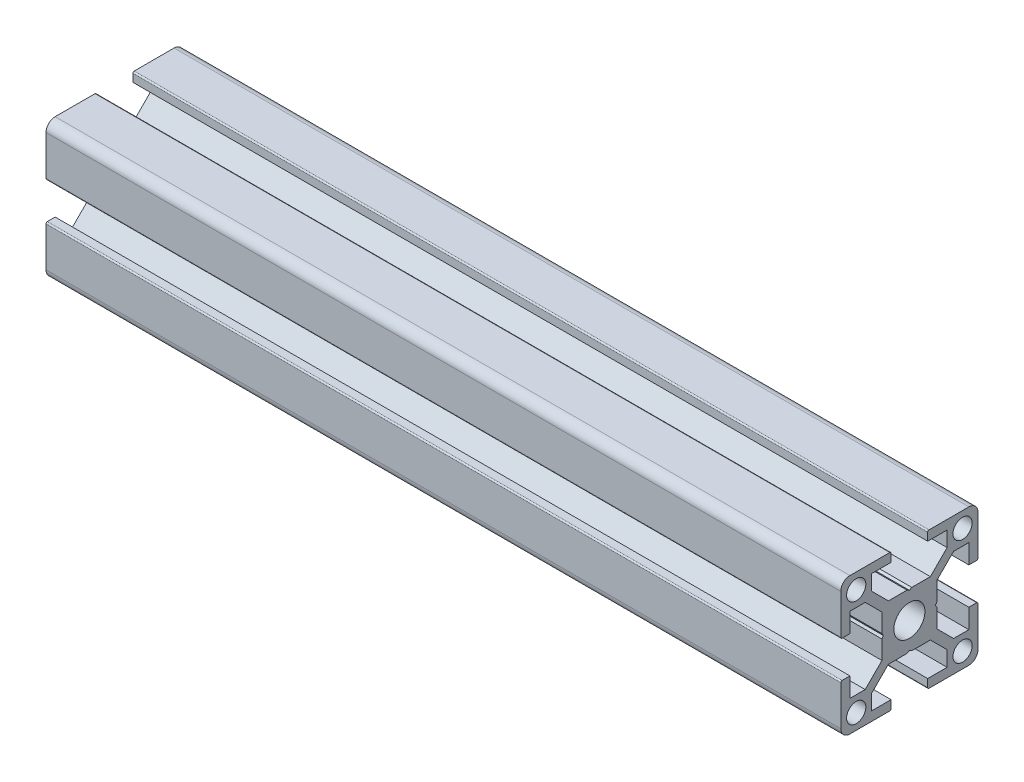
SolidWorks part; units mm, degrees
ref_plane "Front Plane" through (0, 0, 0) normal (0, 0, 1) x (1, 0, 0)
ref_plane "Top Plane" through (0, 0, 0) normal (0, 1, 0) x (1, 0, 0)
ref_plane "Right Plane" through (0, 0, 0) normal (1, 0, 0) x (0, 0, -1)
sketch "Sketch1" plane through (0, 0, 0) normal (0, 0, 1) x (1, 0, 0)
  line L0 (0, 0) -> (173.76, 0)
  dimension "D1" = 173.76
other "30xs6 30X30S6(1)"
ref_plane "Plane1" through (0, 0, 0) normal (1, 0, 0) x (0, 1, 0)
sketch "草图1" plane through (0, 0, 0) normal (1, 0, 0) x (0, 1, 0)
  line L0 (-14.7, 4) -> (-13, 4)
  line L1 (-13, 4) -> (-13, 8.25)
  line L2 (-13, 8.25) -> (-9.6642, 8.25)
  line L3 (-9.6642, 8.25) -> (-6, 4.5858)
  line L4 (-6, 4.5858) -> (-6, 0.5196)
  line L5 (-6, 0.5196) -> (-5.7, 0)
  line L6 (-5.7, 0) -> (-6, -0.5196)
  line L7 (-6, -0.5196) -> (-6, -4.5858)
  line L8 (-6, -4.5858) -> (-9.6642, -8.25)
  line L9 (-9.6642, -8.25) -> (-13, -8.25)
  line L10 (-13, -8.25) -> (-13, -4)
  line L11 (-13, -4) -> (-14.7, -4)
  line L12 (-15, -4.3) -> (-15, -13)
  line L13 (-13, -15) -> (-4.3, -15)
  line L14 (-4, -14.7) -> (-4, -13)
  line L15 (-4, -13) -> (-8.25, -13)
  line L16 (-8.25, -13) -> (-8.25, -9.6642)
  line L17 (-8.25, -9.6642) -> (-4.5858, -6)
  line L18 (-4.5858, -6) -> (-0.5196, -6)
  line L19 (-0.5196, -6) -> (0, -5.7)
  line L20 (0, -5.7) -> (0.5196, -6)
  line L21 (0.5196, -6) -> (4.5858, -6)
  line L22 (4.5858, -6) -> (8.25, -9.6642)
  line L23 (8.25, -9.6642) -> (8.25, -13)
  line L24 (8.25, -13) -> (4, -13)
  line L25 (4, -13) -> (4, -14.7)
  line L26 (4.3, -15) -> (13, -15)
  line L27 (15, -13) -> (15, -4.3)
  line L28 (14.7, -4) -> (13, -4)
  line L29 (13, -4) -> (13, -8.25)
  line L30 (13, -8.25) -> (9.6642, -8.25)
  line L31 (9.6642, -8.25) -> (6, -4.5858)
  line L32 (6, -4.5858) -> (6, -0.5196)
  line L33 (6, -0.5196) -> (5.7, 0)
  line L34 (5.7, 0) -> (6, 0.5196)
  line L35 (6, 0.5196) -> (6, 4.5858)
  line L36 (6, 4.5858) -> (9.6642, 8.25)
  line L37 (9.6642, 8.25) -> (13, 8.25)
  line L38 (13, 8.25) -> (13, 4)
  line L39 (13, 4) -> (14.7, 4)
  line L40 (15, 4.3) -> (15, 13)
  line L41 (13, 15) -> (4.3, 15)
  line L42 (4, 14.7) -> (4, 13)
  line L43 (4, 13) -> (8.25, 13)
  line L44 (8.25, 13) -> (8.25, 9.6642)
  line L45 (8.25, 9.6642) -> (4.5858, 6)
  line L46 (4.5858, 6) -> (0.5196, 6)
  line L47 (0.5196, 6) -> (0, 5.7)
  line L48 (0, 5.7) -> (-0.5196, 6)
  line L49 (-0.5196, 6) -> (-4.5858, 6)
  line L50 (-4.5858, 6) -> (-8.25, 9.6642)
  line L51 (-8.25, 9.6642) -> (-8.25, 13)
  line L52 (-8.25, 13) -> (-4, 13)
  line L53 (-4, 13) -> (-4, 14.7)
  line L54 (-4.3, 15) -> (-13, 15)
  line L55 (-15, 13) -> (-15, 4.3)
  arc A0 (-15, 4.3) -> (-14.7, 4) centre (-14.7, 4.3) ccw
  arc A1 (-14.7, -4) -> (-15, -4.3) centre (-14.7, -4.3) ccw
  arc A2 (-15, -13) -> (-13, -15) centre (-13, -13) ccw
  arc A3 (-4.3, -15) -> (-4, -14.7) centre (-4.3, -14.7) ccw
  arc A4 (4, -14.7) -> (4.3, -15) centre (4.3, -14.7) ccw
  arc A5 (13, -15) -> (15, -13) centre (13, -13) ccw
  arc A6 (15, -4.3) -> (14.7, -4) centre (14.7, -4.3) ccw
  arc A7 (14.7, 4) -> (15, 4.3) centre (14.7, 4.3) ccw
  arc A8 (15, 13) -> (13, 15) centre (13, 13) ccw
  arc A9 (4.3, 15) -> (4, 14.7) centre (4.3, 14.7) ccw
  arc A10 (-4, 14.7) -> (-4.3, 15) centre (-4.3, 14.7) ccw
  arc A11 (-13, 15) -> (-15, 13) centre (-13, 13) ccw
  circle A12 centre (11.625, 11.625) radius 2.1
  circle A13 centre (11.625, -11.625) radius 2.1
  circle A14 centre (0, 0) radius 3.4
  circle A15 centre (-11.625, -11.625) radius 2.1
  circle A16 centre (-11.625, 11.625) radius 2.1
  point P90 (-15, 15)
  point P91 (-0.2598, 14.9121)
  point P92 (15, 15)
  point P93 (15, 0)
  point P94 (15, -15)
  point P95 (0.2598, -15)
  point P96 (-15, -15)
  point P97 (-15, 0)
  point P98 (0, 0)
